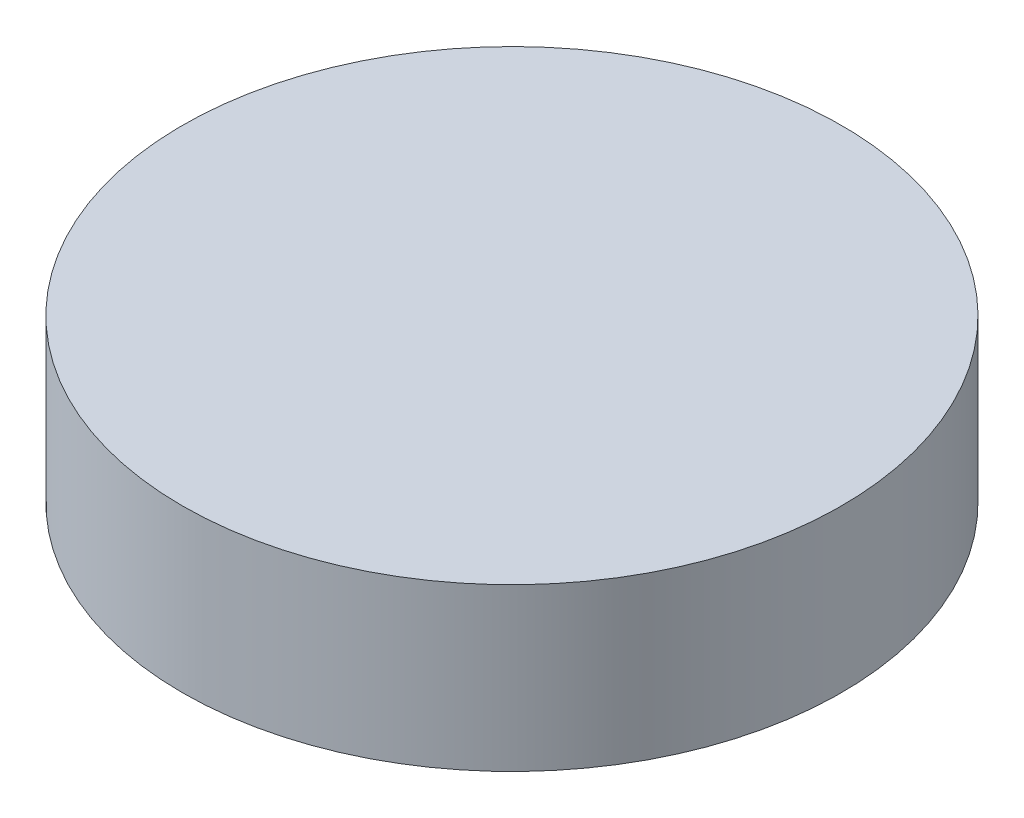
SolidWorks part; units mm, degrees
ref_plane "Front Plane" through (0, 0, 0) normal (0, 0, 1) x (1, 0, 0)
ref_plane "Top Plane" through (0, 0, 0) normal (0, 1, 0) x (1, 0, 0)
ref_plane "Right Plane" through (0, 0, 0) normal (1, 0, 0) x (0, 0, -1)
sketch "Sketch1" plane through (0, 0, 0) normal (0, 1, 0) x (1, 0, 0)
  circle A0 centre (0, 0) radius 110
  dimension "D1" = 220
extrude "Boss-Extrude1" add sketch "Sketch1" along normal blind 54
